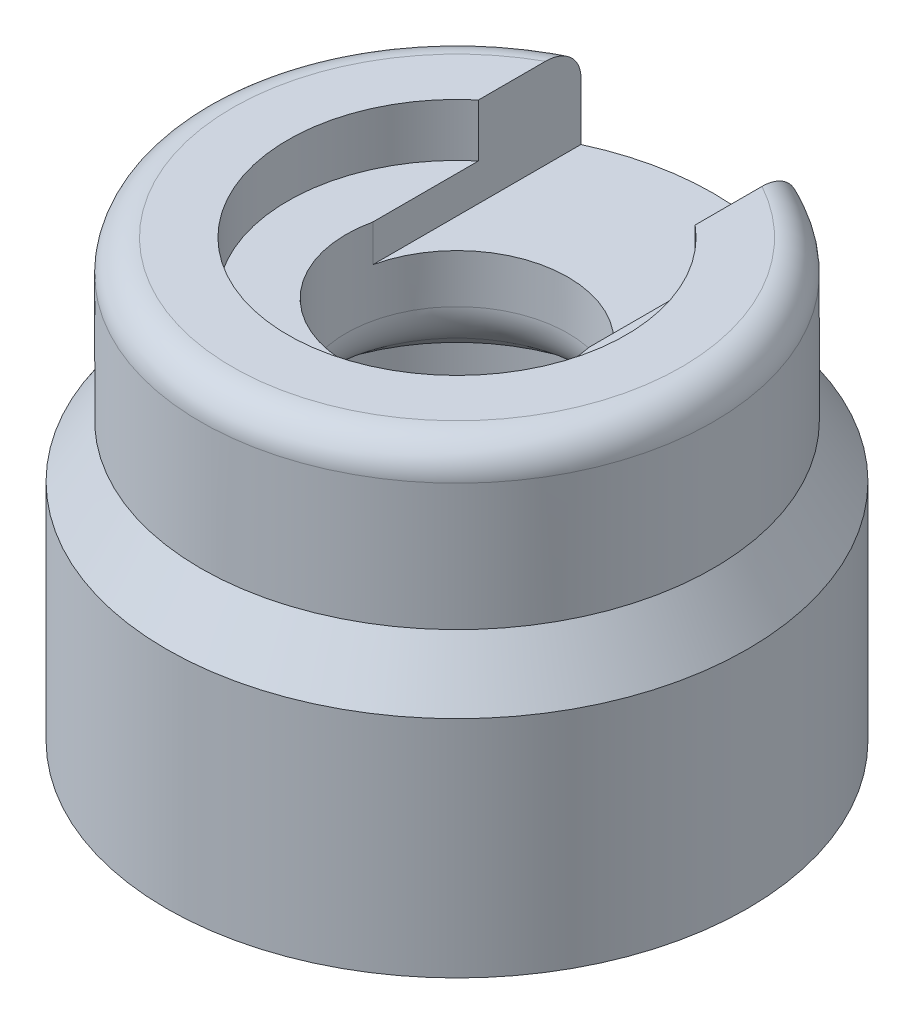
SolidWorks part; units mm, degrees
material "ABS"
ref_plane "Alzado" through (0, 0, 0) normal (0, 0, 1) x (1, 0, 0)
ref_plane "Planta" through (0, 0, 0) normal (0, 1, 0) x (1, 0, 0)
ref_plane "Vista lateral" through (0, 0, 0) normal (1, 0, 0) x (0, 0, -1)
sketch "Croquis1" plane through (0, 0, 0) normal (0, 1, 0) x (1, 0, 0)
  circle A0 centre (0, 0) radius 3.225
  circle A1 centre (0, 0) radius 5.5
  dimension "D1" = 11
  dimension "D2" = 6.45
extrude "Saliente-Extruir1" add sketch "Croquis1" along normal blind 4.25
sketch "Croquis2" plane through (0, 0, 0) normal (0, 0, 1) x (1, 0, 0)
  line L0 (-5.5, 4.25) -> (-4.85, 5.25)
  line L1 (-4.85, 5.25) -> (-2.1, 5.25)
  line L2 (-2.1, 5.25) -> (-2.1, 5.15)
  line L3 (-2.1, 5.15) -> (-3.225, 4.25)
  line L4 (5.5, 4.25) -> (-5.5, 4.25) construction
  line L5 (0, 0) -> (0, 6.8987) construction
  line L6 (-5.5, 4.25) -> (-3.225, 4.25)
  dimension "D1" = 4.2
  dimension "D2" = 0.1
  dimension "D3" = 2.75
  dimension "D4" = 1
revolve "Revolución1" add sketch "Croquis2" angle 360 about L5
sketch "Croquis3" plane through (0, 5.25, 0) normal (0, 1, 0) x (1, 0, 0)
  circle A0 centre (0, 0) radius 2.1
  circle A1 centre (0, 0) radius 4.85
  circle A2 centre (0, 0) radius 4.85 construction
  circle A3 centre (0, 0) radius 2.1 construction
extrude "Saliente-Extruir2" add sketch "Croquis3" along normal blind 3
fillet "Redondeo1" radius 0.6 1 edges at (0, 8.25, 4.85)
sketch "Croquis4" plane through (0, 8.25, 0) normal (0, 1, 0) x (1, 0, 0)
  circle A0 centre (0, 0) radius 3.2
  dimension "D1" = 6.4
extrude "Cortar-Extruir1" cut sketch "Croquis4" against normal blind 1
sketch "Croquis5" plane through (0, 7.25, 0) normal (0, 1, 0) x (1, 0, 0)
  line L1 (-2.05, 0.0031) -> (2.05, 0.0031)
  line L2 (-2.05, 0.0031) -> (-2.05, 5.0031)
  line L3 (-2.05, 5.0031) -> (2.05, 5.0031)
  line L4 (2.05, 0.0031) -> (2.05, 5.0031)
  point P4 (0, 5.0031)
  dimension "D1" = 4.1
  dimension "D2" = 5
extrude "Cortar-Extruir2" cut sketch "Croquis5" along normal through all from offset 0.7 offset against normal yes
fillet "Redondeo2" radius 1 1 edges at (0, 5.15, -2.1)
fillet "Redondeo3" radius 0.75 1 edges at (0, 0, 3.225)
